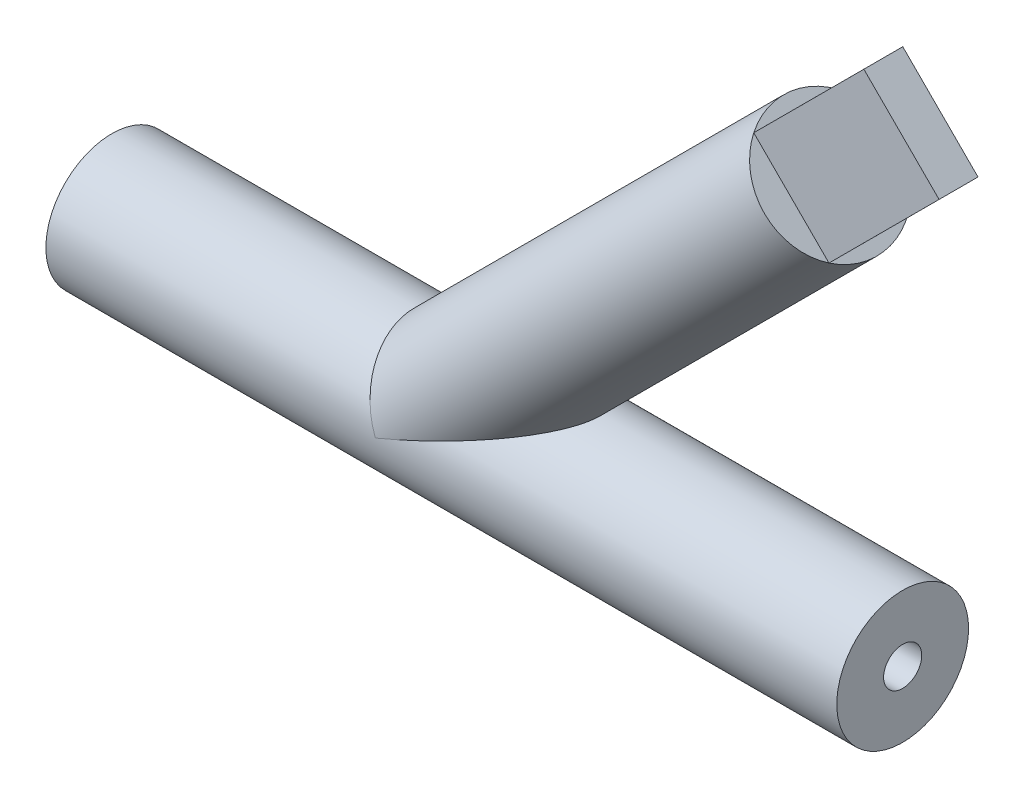
SolidWorks part; units mm, degrees
ref_plane "Front Plane" through (0, 0, 0) normal (0, 0, 1) x (1, 0, 0)
ref_plane "Top Plane" through (0, 0, 0) normal (0, 1, 0) x (1, 0, 0)
ref_plane "Right Plane" through (0, 0, 0) normal (1, 0, 0) x (0, 0, -1)
sketch "Sketch1" plane through (0, 0, 0) normal (1, 0, 0) x (0, 0, -1)
  circle A0 centre (0, 0) radius 12.7
  dimension "D1" = 25.4
extrude "Boss-Extrude1" add sketch "Sketch1" along normal blind 152.4
sketch "Sketch4" plane through (0, 0, 0) normal (0, 1, 0) x (1, 0, 0)
  line L0 (63.5, -34.1123) -> (63.5, 43.0803)
  line L1 (0, 12.7) -> (0, -12.7) construction
  circle A0 centre (63.5, 0) radius 15
  dimension "D1" = 63.5
ref_plane "Plane1" through (31.75, 31.75, 0) normal (0.7071, 0.7071, 0) x (0.7071, -0.7071, 0)
sketch "Sketch5" plane through (31.75, 31.75, 0) normal (0.7071, 0.7071, 0) x (0.7071, -0.7071, 0)
  circle A0 centre (44.9013, 0) radius 12.7
  dimension "D1" = 25.4
extrude "Boss-Extrude3" add sketch "Sketch5" along normal blind 106 contours A0
sketch "Sketch6" plane through (106.7033, 106.7033, 0) normal (0.7071, 0.7071, 0) x (0, 0, -1)
  line L1 (0, -55.1513) -> (-7.5, -55.1513)
  line L2 (-7.5, -34.6513) -> (-7.5, -55.1513)
  line L4 (0, -55.1513) -> (0, -34.6513)
  line L7 (0, -34.6513) -> (-7.5, -34.6513)
  line L8 (-7.5, -55.1513) -> (-7.5, -34.6513)
  point P2 (0, -44.9013)
  circle M1 centre (0, -44.9013) radius 12.7
  dimension "D1" = 20.5
  dimension "D2" = 7.5
extrude "Boss-Extrude5" add sketch "Sketch6" along normal blind 30 contours L4 L2 M1
sketch "Sketch7" plane through (0, 0, 0) normal (-1, 0, 0) x (0, 0, 1)
  circle A0 centre (0, 0) radius 3.675
  dimension "D1" = 7.35
extrude "Cut-Extrude1" cut sketch "Sketch7" against normal blind 152.4
